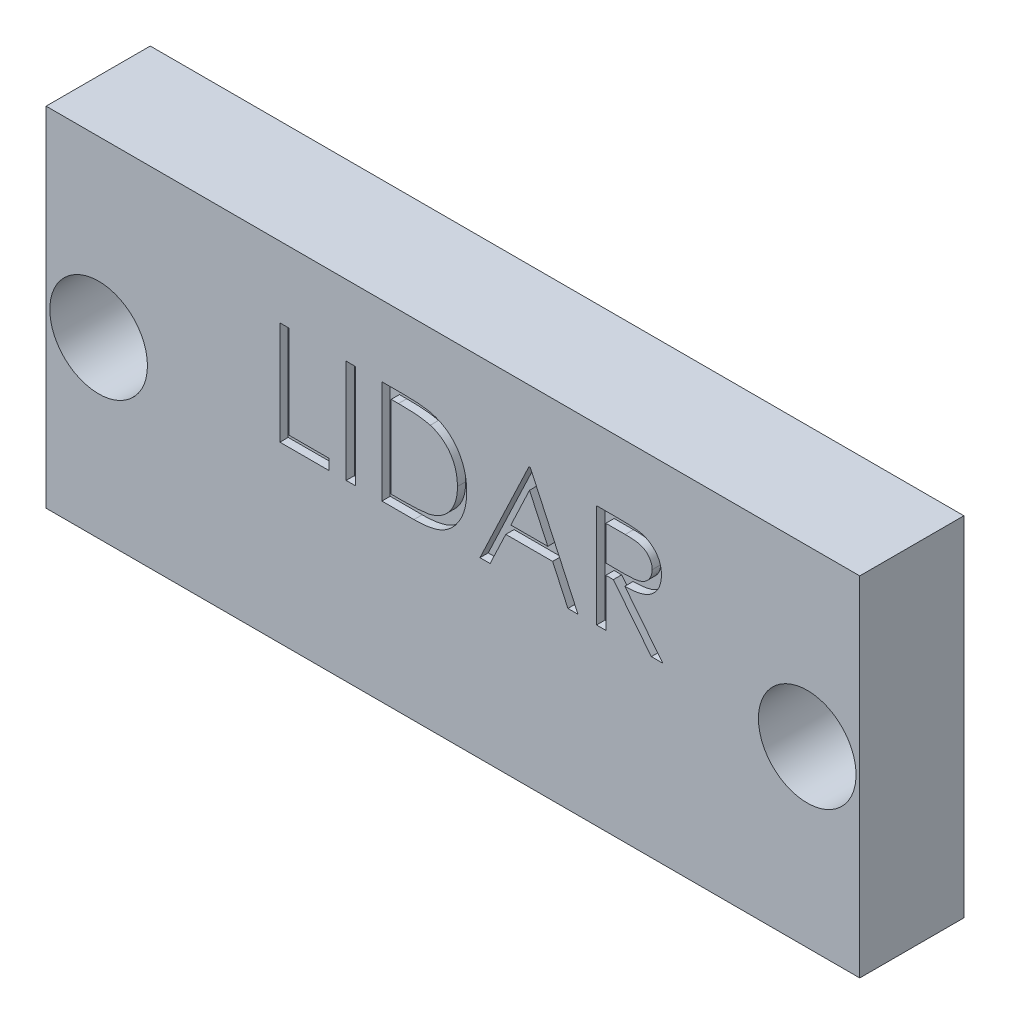
SolidWorks part; units mm, degrees
ref_plane "Front Plane" through (0, 0, 0) normal (0, 0, 1) x (1, 0, 0)
ref_plane "Top Plane" through (0, 0, 0) normal (0, 1, 0) x (1, 0, 0)
ref_plane "Right Plane" through (0, 0, 0) normal (1, 0, 0) x (0, 0, -1)
sketch "Sketch2" plane through (0, 0, 0) normal (0, 0, 1) x (1, 0, 0)
  line L1 (-12.4277, 0) -> (12.5723, 0)
  line L2 (-12.4277, 0) -> (-12.4277, -10.7)
  line L3 (-12.4277, -10.7) -> (12.5723, -10.7)
  line L4 (12.5723, 0) -> (12.5723, -10.7)
  dimension "D1" = 25
  dimension "D2" = 10.7
extrude "Boss-Extrude1" add sketch "Sketch2" along normal blind 3.2
sketch "Sketch3" plane through (0, 0, 3.2) normal (0, 0, 1) x (1, 0, 0)
  line L0 (-12.4277, -5.35) -> (12.5723, -5.35) construction
  line L1 (-12.4277, 0) -> (-12.4277, -10.7) construction
  line L2 (12.5723, -10.7) -> (12.5723, 0) construction
  line L3 (0.0723, 0) -> (0.0723, -10.7) construction
  line L4 (12.5723, 0) -> (-12.4277, 0) construction
  line L5 (-12.4277, -10.7) -> (12.5723, -10.7) construction
  circle A0 centre (-10.814, -5.35) radius 1.5
  circle A1 centre (10.9586, -5.35) radius 1.5
  dimension "D1" = 3
extrude "Cut-Extrude2" cut sketch "Sketch3" against normal blind 3.2
sketch "Sketch4" plane through (0, 0, 3.2) normal (0, 0, 1) x (1, 0, 0)
  line L0 (-9.314, -5.35) -> (9.4586, -5.35) construction
  circle A0 centre (-10.814, -5.35) radius 1.5 construction
  circle A1 centre (10.9586, -5.35) radius 1.5 construction
  text T0 "   LIDAR"
extrude "Cut-Extrude3" cut sketch "Sketch4" against normal blind 0.254
